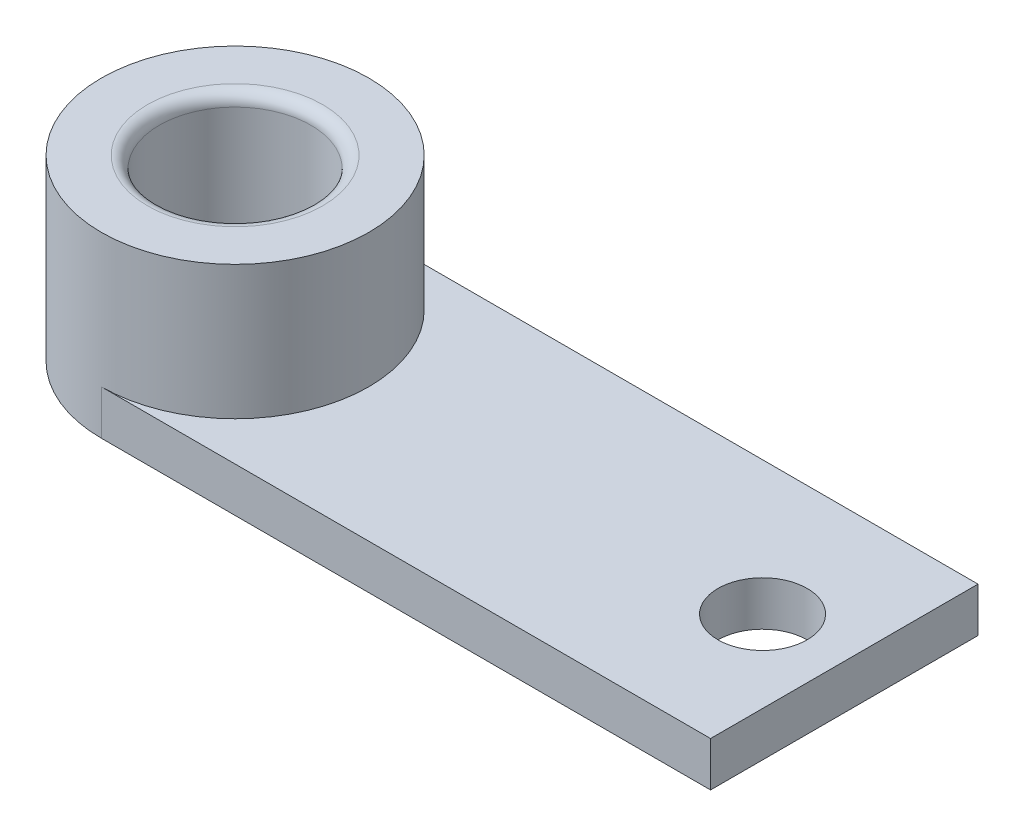
SolidWorks part; units mm, degrees
ref_plane "Front Plane" through (0, 0, 0) normal (0, 0, 1) x (1, 0, 0)
ref_plane "Top Plane" through (0, 0, 0) normal (0, 1, 0) x (1, 0, 0)
ref_plane "Right Plane" through (0, 0, 0) normal (1, 0, 0) x (0, 0, -1)
sketch "Sketch2" plane through (0, 0, 0) normal (0, 1, 0) x (1, 0, 0)
  line L0 (0, 0) -> (25, 0)
  line L1 (25, 0) -> (25, 9)
  line L2 (25, 9) -> (0, 9)
  line L3 (0, 9) -> (0, 0)
  line L4 (0, 4.5) -> (4.5, 4.5) construction
  line L5 (25, 4.5) -> (22.25, 4.5) construction
  dimension "D1" = 25
  dimension "D2" = 9
  dimension "D3" = 4.5
  dimension "D5" = 2.75
extrude "Boss-Extrude3" add sketch "Sketch2" along normal blind 6
sketch "Sketch3" plane through (0, 6, 0) normal (0, 1, 0) x (1, 0, 0)
  line L0 (0, 4.5) -> (4.5, 4.5) construction
  line L1 (0, 9) -> (0, 0) construction
  line L2 (25, 4.5) -> (22.25, 4.5) construction
  line L3 (25, 0) -> (25, 9) construction
  circle A0 centre (4.5, 4.5) radius 2.55
  circle A1 centre (22.25, 4.5) radius 1.75
  dimension "D3" = 5.1
  dimension "D4" = 3.5
  dimension "D1" = 4.5
  dimension "D2" = 2.75
extrude "Cut-Extrude1" cut sketch "Sketch3" against normal blind 5 contours A0
sketch "Sketch4" plane through (0, 6, 0) normal (0, 1, 0) x (1, 0, 0)
  line L0 (25, 4.5) -> (22.25, 4.5) construction
  line L1 (25, 0) -> (25, 9) construction
  circle A0 centre (22.25, 4.5) radius 1.5
  dimension "D2" = 3
  dimension "D1" = 2.75
extrude "Cut-Extrude2" cut sketch "Sketch4" against normal through all both and the other way through all
sketch "Sketch5" plane through (0, 6, 0) normal (0, 1, 0) x (1, 0, 0)
  line L0 (4.5, 9) -> (0, 9)
  line L1 (0, 9) -> (0, 4.5)
  line L2 (0, 4.5) -> (0, 0)
  line L3 (0, 0) -> (4.5, 0)
  line L4 (4.5, 0) -> (25, 0)
  line L5 (25, 0) -> (25, 9)
  line L6 (25, 9) -> (4.5, 9)
  circle A0 centre (4.5, 4.5) radius 4.5
  circle M9 centre (22.25, 4.5) radius 1.5
  line M12 (0, 0) -> (25, 0)
  line M13 (25, 0) -> (25, 9)
  line M14 (25, 9) -> (0, 9)
extrude "Cut-Extrude3" cut sketch "Sketch5" against normal blind 4.5 contours A0 M12 M13 M14 M9
sketch "Sketch6" plane through (0, 6, 0) normal (0, 1, 0) x (1, 0, 0)
  line L0 (4.5, 9) -> (0, 9)
  line L1 (0, 9) -> (0, 0)
  line L2 (0, 0) -> (4.5, 0)
  circle A0 centre (4.5, 4.5) radius 4.5
  line M2 (0, 0) -> (4.5, 0)
  line M4 (4.5, 9) -> (0, 9)
  line M5 (0, 9) -> (0, 0)
extrude "Cut-Extrude4" cut sketch "Sketch6" against normal through all contours A0 M4 M5 | A0 L1 M2
sketch "Sketch7" plane through (0, 6, 0) normal (0, 1, 0) x (1, 0, 0)
  circle A0 centre (4.5, 4.5) radius 2.8
  circle A2 centre (4.5, 4.5) radius 2.6
  dimension "D1" = 5.6
fillet "Fillet2" radius 0.4 1 edges at (4.5, 6, -1.95)
sketch "Sketch8" plane through (0, 0, 0) normal (0, -1, 0) x (1, 0, 0)
  circle A0 centre (4.5, -4.5) radius 1
  dimension "D1" = 2
extrude "Cut-Extrude5" cut sketch "Sketch8" against normal through all
